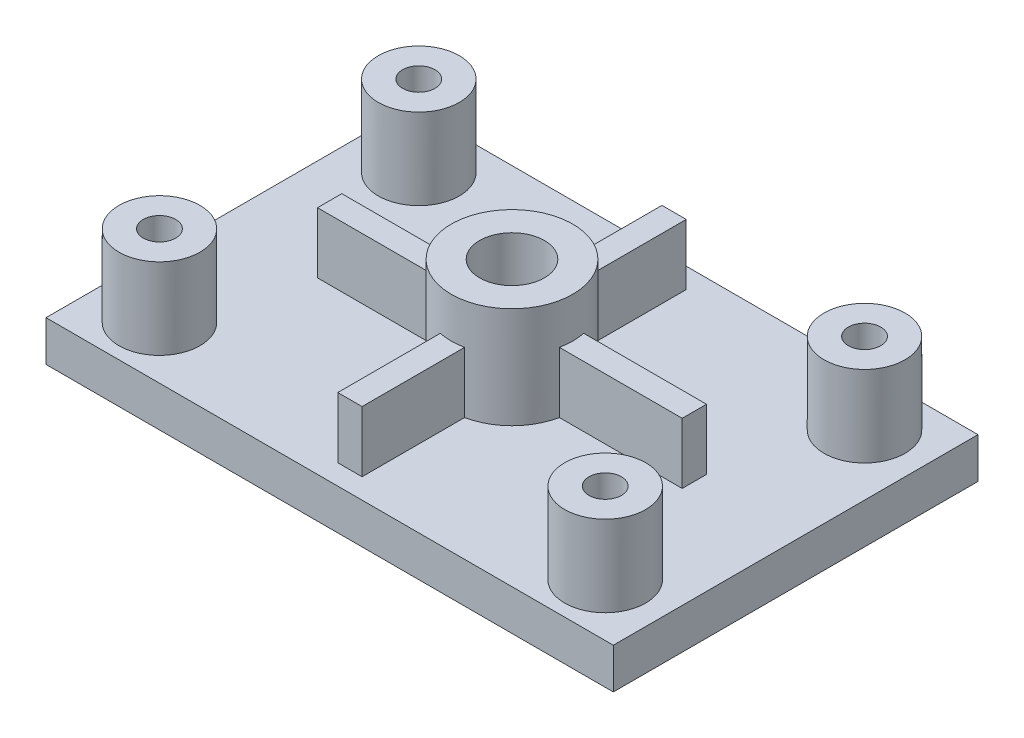
SolidWorks part; units mm, degrees
ref_plane "前视基准面" through (0, 0, 0) normal (0, 0, 1) x (1, 0, 0)
ref_plane "上视基准面" through (0, 0, 0) normal (0, 1, 0) x (1, 0, 0)
ref_plane "右视基准面" through (0, 0, 0) normal (1, 0, 0) x (0, 0, -1)
sketch "草图1" plane through (0, 0, 0) normal (0, 1, 0) x (1, 0, 0)
  line L0 (-70, 45) -> (70, 45)
  line L1 (70, 45) -> (70, -45)
  line L2 (70, -45) -> (-70, -45)
  line L3 (-70, -45) -> (-70, 45)
extrude "凸台-拉伸1" add sketch "草图1" along normal blind 10
sketch "草图2" plane through (0, 0, 0) normal (0, 1, 0) x (1, 0, 0)
  line L0 (-40, 25) -> (40, 25)
  line L1 (40, 25) -> (40, -25)
  line L2 (40, -25) -> (-40, -25)
  line L3 (-40, -25) -> (-40, 25)
extrude "切除-拉伸1" cut sketch "草图2" along normal blind 4
ref_plane "基准面1" through (0, 10, 0) normal (0, 1, 0) x (1, 0, 0)
sketch "草图3" plane through (0, 10, 0) normal (0, 1, 0) x (1, 0, 0)
  line L0 (-45, 3) -> (45, 3)
  line L1 (45, 3) -> (45, -3)
  line L2 (45, -3) -> (-45, -3)
  line L3 (-45, -3) -> (-45, 3)
extrude "凸台-拉伸2" add sketch "草图3" along normal blind 15
sketch "草图4" plane through (0, 10, 0) normal (0, 1, 0) x (1, 0, 0)
  line L0 (-3, 40) -> (3, 40)
  line L1 (3, 40) -> (3, -40)
  line L2 (3, -40) -> (-3, -40)
  line L3 (-3, -40) -> (-3, 40)
extrude "凸台-拉伸3" add sketch "草图4" along normal blind 15
sketch "草图5" plane through (0, 10, 0) normal (0, 1, 0) x (1, 0, 0)
  circle A0 centre (-55, 32) radius 10
  circle A1 centre (55, 32) radius 10
  circle A2 centre (-55, -32) radius 10
  circle A3 centre (55, -32) radius 10
extrude "凸台-拉伸4" add sketch "草图5" along normal blind 20
sketch "草图6" plane through (0, 10, 0) normal (0, 1, 0) x (1, 0, 0)
  circle A0 centre (0, 0) radius 15
extrude "凸台-拉伸5" add sketch "草图6" along normal blind 25
ref_plane "基准面2" through (0, 30, 0) normal (0, 1, 0) x (1, 0, 0)
sketch "草图7" plane through (0, 30, 0) normal (0, 1, 0) x (1, 0, 0)
  circle A0 centre (-55, 32) radius 4
  circle A1 centre (55, 32) radius 4
  circle A2 centre (-55, -32) radius 4
  circle A3 centre (55, -32) radius 4
extrude "切除-拉伸2" cut sketch "草图7" against normal mid plane 282
ref_plane "基准面3" through (0, 35, 0) normal (0, 1, 0) x (1, 0, 0)
sketch "草图8" plane through (0, 35, 0) normal (0, 1, 0) x (1, 0, 0)
  circle A0 centre (0, 0) radius 8
extrude "切除-拉伸3" cut sketch "草图8" against normal blind 20
